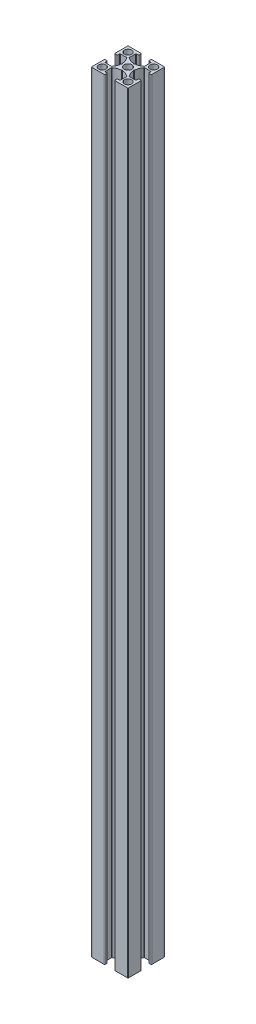
SolidWorks part; units mm, degrees
ref_plane "정면도" through (0, 0, 0) normal (0, 0, 1) x (1, 0, 0)
ref_plane "평면도" through (0, 0, 0) normal (0, 1, 0) x (1, 0, 0)
ref_plane "우측면도" through (0, 0, 0) normal (1, 0, 0) x (0, 0, -1)
sketch "스케치1" plane through (0, 0, 0) normal (0, 1, 0) x (1, 0, 0)
  line B0 (4.15, 4.9427) -> (4.15, 8.2)
  line B1 (3.85, 8.5) -> (2.95, 8.5)
  line B2 (2.65, 8.8) -> (2.65, 9.7)
  line B3 (2.95, 10) -> (9.7, 10)
  line B4 (10, 9.7) -> (10, 2.95)
  line B5 (9.7, 2.65) -> (8.8, 2.65)
  line B6 (8.5, 2.95) -> (8.5, 3.85)
  line B7 (8.2, 4.15) -> (4.9427, 4.15)
  line B8 (3.3073, 0.3073) -> (3, 0)
  line B9 (3, 0) -> (3.3073, -0.3073)
  line B10 (4.9427, -4.15) -> (8.2, -4.15)
  line B11 (8.5, -3.85) -> (8.5, -2.95)
  line B12 (8.8, -2.65) -> (9.7, -2.65)
  line B13 (10, -2.95) -> (10, -9.7)
  line B14 (9.7, -10) -> (2.95, -10)
  line B15 (2.65, -9.7) -> (2.65, -8.8)
  line B16 (2.95, -8.5) -> (3.85, -8.5)
  line B17 (4.15, -8.2) -> (4.15, -4.9427)
  line B18 (0.3073, -3.3073) -> (0, -3)
  line B19 (0, -3) -> (-0.3073, -3.3073)
  line B20 (-4.15, -4.9427) -> (-4.15, -8.2)
  line B21 (-3.85, -8.5) -> (-2.95, -8.5)
  line B22 (-2.65, -8.8) -> (-2.65, -9.7)
  line B23 (-2.95, -10) -> (-9.7, -10)
  line B24 (-10, -9.7) -> (-10, -2.95)
  line B25 (-9.7, -2.65) -> (-8.8, -2.65)
  line B26 (-8.5, -2.95) -> (-8.5, -3.85)
  line B27 (-8.2, -4.15) -> (-4.9427, -4.15)
  line B28 (-3.3073, -0.3073) -> (-3, 0)
  line B29 (-3, 0) -> (-3.3073, 0.3073)
  line B30 (-4.9427, 4.15) -> (-8.2, 4.15)
  line B31 (-8.5, 3.85) -> (-8.5, 2.95)
  line B32 (-8.8, 2.65) -> (-9.7, 2.65)
  line B33 (-10, 2.95) -> (-10, 9.7)
  line B34 (-9.7, 10) -> (-2.95, 10)
  line B35 (-2.65, 9.7) -> (-2.65, 8.8)
  line B36 (-2.95, 8.5) -> (-3.85, 8.5)
  line B37 (-4.15, 8.2) -> (-4.15, 4.9427)
  line B38 (-0.3073, 3.3073) -> (0, 3)
  line B39 (0, 3) -> (0.3073, 3.3073)
  line B40 (-9.5, 7) -> (-4.5, 7) construction
  line B41 (-7, 9.5) -> (-7, 4.5) construction
  line B42 (-9.5, -7) -> (-4.5, -7) construction
  line B43 (-7, -9.5) -> (-7, -4.5) construction
  line B44 (9.5, 7) -> (4.5, 7) construction
  line B45 (7, 9.5) -> (7, 4.5) construction
  line B46 (7, -9.5) -> (7, -4.5) construction
  line B47 (9.5, -7) -> (4.5, -7) construction
  circle B48 centre (0, 0) radius 2.15
  arc B49 (4.15, 8.2) -> (3.85, 8.5) centre (3.85, 8.2) ccw
  arc B50 (2.65, 8.8) -> (2.95, 8.5) centre (2.95, 8.8) ccw
  arc B51 (2.95, 10) -> (2.65, 9.7) centre (2.95, 9.7) ccw
  arc B52 (10, 9.7) -> (9.7, 10) centre (9.7, 9.7) ccw
  arc B53 (9.7, 2.65) -> (10, 2.95) centre (9.7, 2.95) ccw
  arc B54 (8.5, 2.95) -> (8.8, 2.65) centre (8.8, 2.95) ccw
  arc B55 (8.5, 3.85) -> (8.2, 4.15) centre (8.2, 3.85) ccw
  arc B56 (4.9427, 4.15) -> (4.7078, 4.0366) centre (4.9427, 3.85) ccw
  arc B57 (4.7078, 4.0366) -> (3.3073, 0.3073) centre (9.7908, 0) ccw
  arc B58 (3.3073, -0.3073) -> (4.7078, -4.0366) centre (9.7908, 0) ccw
  arc B59 (4.7078, -4.0366) -> (4.9427, -4.15) centre (4.9427, -3.85) ccw
  arc B60 (8.2, -4.15) -> (8.5, -3.85) centre (8.2, -3.85) ccw
  arc B61 (8.8, -2.65) -> (8.5, -2.95) centre (8.8, -2.95) ccw
  arc B62 (10, -2.95) -> (9.7, -2.65) centre (9.7, -2.95) ccw
  arc B63 (9.7, -10) -> (10, -9.7) centre (9.7, -9.7) ccw
  arc B64 (2.65, -9.7) -> (2.95, -10) centre (2.95, -9.7) ccw
  arc B65 (2.95, -8.5) -> (2.65, -8.8) centre (2.95, -8.8) ccw
  arc B66 (3.85, -8.5) -> (4.15, -8.2) centre (3.85, -8.2) ccw
  arc B67 (4.15, -4.9427) -> (4.0366, -4.7078) centre (3.85, -4.9427) ccw
  arc B68 (4.0366, -4.7078) -> (0.3073, -3.3073) centre (0, -9.7908) ccw
  arc B69 (-0.3073, -3.3073) -> (-4.0366, -4.7078) centre (0, -9.7908) ccw
  arc B70 (-4.0366, -4.7078) -> (-4.15, -4.9427) centre (-3.85, -4.9427) ccw
  arc B71 (-4.15, -8.2) -> (-3.85, -8.5) centre (-3.85, -8.2) ccw
  arc B72 (-2.65, -8.8) -> (-2.95, -8.5) centre (-2.95, -8.8) ccw
  arc B73 (-2.95, -10) -> (-2.65, -9.7) centre (-2.95, -9.7) ccw
  arc B74 (-10, -9.7) -> (-9.7, -10) centre (-9.7, -9.7) ccw
  arc B75 (-9.7, -2.65) -> (-10, -2.95) centre (-9.7, -2.95) ccw
  arc B76 (-8.5, -2.95) -> (-8.8, -2.65) centre (-8.8, -2.95) ccw
  arc B77 (-8.5, -3.85) -> (-8.2, -4.15) centre (-8.2, -3.85) ccw
  arc B78 (-4.9427, -4.15) -> (-4.7078, -4.0366) centre (-4.9427, -3.85) ccw
  arc B79 (-4.7078, -4.0366) -> (-3.3073, -0.3073) centre (-9.7908, 0) ccw
  arc B80 (-3.3073, 0.3073) -> (-4.7078, 4.0366) centre (-9.7908, 0) ccw
  arc B81 (-4.7078, 4.0366) -> (-4.9427, 4.15) centre (-4.9427, 3.85) ccw
  arc B82 (-8.2, 4.15) -> (-8.5, 3.85) centre (-8.2, 3.85) ccw
  arc B83 (-8.8, 2.65) -> (-8.5, 2.95) centre (-8.8, 2.95) ccw
  arc B84 (-10, 2.95) -> (-9.7, 2.65) centre (-9.7, 2.95) ccw
  arc B85 (-9.7, 10) -> (-10, 9.7) centre (-9.7, 9.7) ccw
  arc B86 (-2.65, 9.7) -> (-2.95, 10) centre (-2.95, 9.7) ccw
  arc B87 (-2.95, 8.5) -> (-2.65, 8.8) centre (-2.95, 8.8) ccw
  arc B88 (-3.85, 8.5) -> (-4.15, 8.2) centre (-3.85, 8.2) ccw
  arc B89 (-4.15, 4.9427) -> (-4.0366, 4.7078) centre (-3.85, 4.9427) ccw
  arc B90 (-4.0366, 4.7078) -> (-0.3073, 3.3073) centre (0, 9.7908) ccw
  arc B91 (0.3073, 3.3073) -> (4.0366, 4.7078) centre (0, 9.7908) ccw
  arc B92 (4.0366, 4.7078) -> (4.15, 4.9427) centre (3.85, 4.9427) ccw
  circle B93 centre (-7, 7) radius 2
  circle B94 centre (-7, -7) radius 2
  circle B95 centre (7, 7) radius 2
  circle B96 centre (7, -7) radius 2
sketch_block_instance "블록1-1"
sketch_block "블록1"
extrude "보스-돌출1" add sketch "스케치1" along normal blind 420 contours B92 B91 B39 B38 B90 B89 B37 B88 B36 B87 B35 B86 B34 B85 B33 B84 B32 B83 B31 B82 B30 B81 B80 B29 B28 B79 B78 B27 B77 B26 B76 B25 B75 B24 B74 B23 B73 B22 B72 B21 B71 B20 B70 B69 B19 B18 B68 B67 B17 B66 B16
